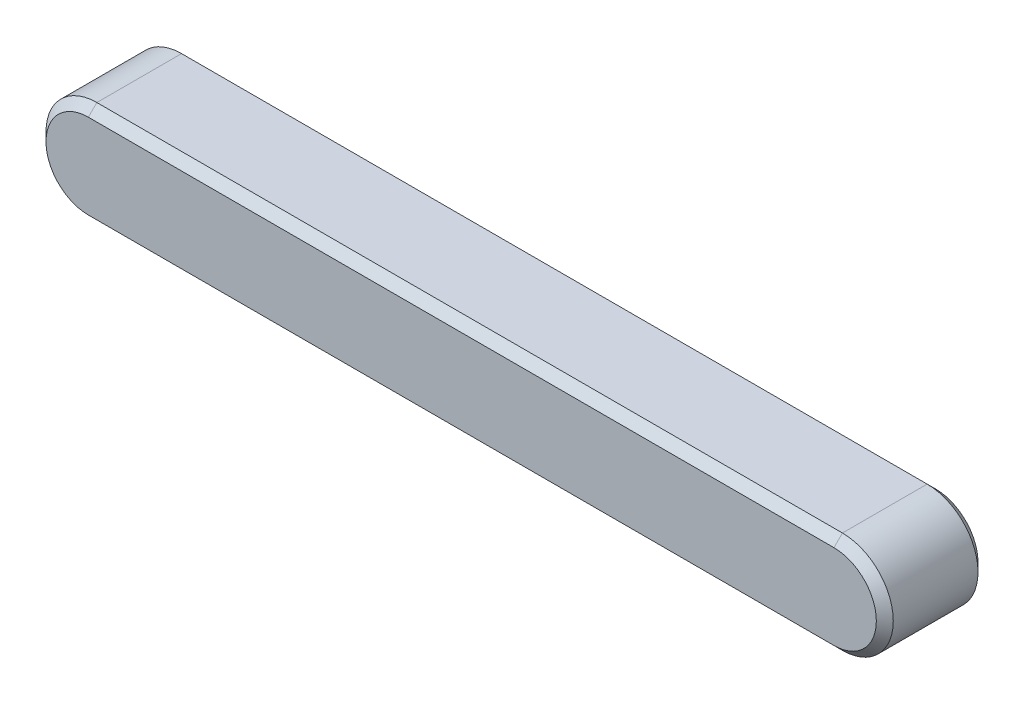
SolidWorks part; units mm, degrees
ref_plane "Front" through (0, 0, 0) normal (0, 0, 1) x (1, 0, 0)
ref_plane "Top" through (0, 0, 0) normal (0, 1, 0) x (1, 0, 0)
ref_plane "Right" through (0, 0, 0) normal (1, 0, 0) x (0, 0, -1)
sketch "Sketch1" plane through (0, 0, 0) normal (0, 0, 1) x (1, 0, 0)
  line L0 (-22, 1.5) -> (0, 1.5)
  line L1 (0, -1.5) -> (-22, -1.5)
  arc A0 (0, 1.5) -> (0, -1.5) centre (0, 0) cw
  arc A1 (-22, -1.5) -> (-22, 1.5) centre (-22, 0) cw
  dimension "L" = 25
  dimension "b" = 3
extrude "BaseKey" add sketch "Sketch1" along normal mid plane 3
sketch "Sketch2" plane through (0, 0, 0) normal (0, 0, 1) x (1, 0, 0)
  line L1 (-23.5, 1.5) -> (1.5, 1.5)
  line L2 (-23.5, 1.5) -> (-23.5, -1.5)
  line L3 (-23.5, -1.5) -> (1.5, -1.5)
  line L4 (1.5, 1.5) -> (1.5, -1.5)
  line L6 (0, -1.5) -> (-22, -1.5) construction
  line L7 (-22, 1.5) -> (0, 1.5) construction
  arc A2 (0, -1.5) -> (0, 1.5) centre (0, 0) ccw construction
  arc A3 (-22, 1.5) -> (-22, -1.5) centre (-22, 0) ccw construction
extrude "Extrude1" [suppressed] add sketch "Sketch2" along normal mid plane 3
sketch "Sketch3" plane through (0, 0, 0) normal (0, 0, 1) x (1, 0, 0)
  line L0 (1.5, 1.5) -> (-22, 1.5)
  line L1 (-22, -1.5) -> (1.5, -1.5)
  line L2 (1.5, -1.5) -> (1.5, 1.5)
  line L5 (-22, 1.5) -> (0, 1.5) construction
  arc A0 (-22, 1.5) -> (-22, -1.5) centre (-22, 0) ccw
  arc A1 (0, -1.5) -> (0, 1.5) centre (0, 0) ccw construction
  arc A4 (-22, 1.5) -> (-22, -1.5) centre (-22, 0) ccw construction
extrude "Extrude2" [suppressed] add sketch "Sketch3" along normal mid plane 3
chamfer "Chamfer1" distance 0.25 angle 45 8 edges at (1.5, 0, -1.5) (-11, -1.5, -1.5) (-23.5, 0, -1.5) (-11, 1.5, -1.5) (-23.5, 0, 1.5) (-11, -1.5, 1.5) (1.5, 0, 1.5) (-11, 1.5, 1.5)
equation "\"D1@Extrude1\"=\"h@BaseKey\""
equation "\"D1@Extrude2\"=\"h@BaseKey\""
